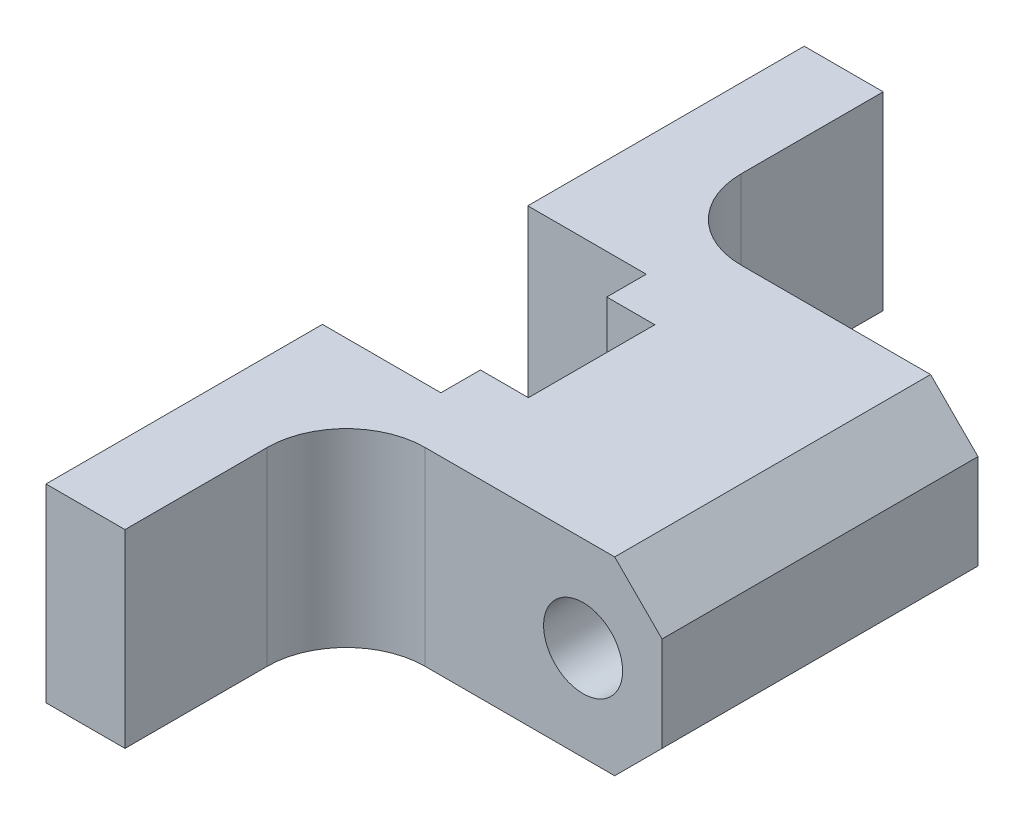
SolidWorks part; units mm, degrees
ref_plane "Спереди" through (0, 0, 0) normal (0, 0, 1) x (1, 0, 0)
ref_plane "Сверху" through (0, 0, 0) normal (0, 1, 0) x (1, 0, 0)
ref_plane "Справа" through (0, 0, 0) normal (1, 0, 0) x (0, 0, -1)
sketch "Эскиз1" plane through (0, 0, 0) normal (1, 0, 0) x (0, 0, -1)
  line L0 (-20, -40.6306) -> (-68.5325, -40.6306) construction
  line L1 (-20, -34.6306) -> (0, -34.6306)
  line L2 (-20, -34.6306) -> (-20, -46.6306)
  line L3 (-20, -46.6306) -> (0, -46.6306)
  line L4 (0, -34.6306) -> (0, -46.6306)
  point P0 (0, 0)
  dimension "D1" = 6
  dimension "D2" = 6
extrude "Вытянуть1" add sketch "Эскиз1" along normal blind 25
sketch "Эскиз5" plane through (0, 0, 20) normal (0, 0, 1) x (1, 0, 0)
  line L0 (0, -34.6306) -> (0, -46.6306) construction
  circle A0 centre (20, -40.6306) radius 2.5
  dimension "D1" = 20
extrude "Вырез-Вытянуть2" cut sketch "Эскиз5" against normal through all
sketch "Эскиз6" plane through (0, 0, 0) normal (-1, 0, 0) x (0, 0, 1)
  line L0 (10, -34.6306) -> (10, -26.4404) construction
  line L1 (20, -34.6306) -> (34, -34.6306)
  line L2 (20, -34.6306) -> (20, -46.6306)
  line L3 (20, -46.6306) -> (34, -46.6306)
  line L4 (34, -34.6306) -> (34, -46.6306)
  line L6 (0, -46.6306) -> (-14, -46.6306)
  line L7 (0, -34.6306) -> (0, -46.6306)
  line L8 (-14, -34.6306) -> (-14, -46.6306)
  line L9 (0, -34.6306) -> (-14, -34.6306)
extrude "Вытянуть2" add sketch "Эскиз6" against normal blind 5
chamfer "Фаска1" distance 3 angle 45 2 edges at (25, -46.6306, 10) (25, -34.6306, 10)
sketch "Эскиз8" plane through (0, -34.6306, 0) normal (0, 1, 0) x (1, 0, 0)
  line L0 (0, -10) -> (-8.3082, -10) construction
  line L2 (0, 14) -> (0, -34) construction
  line L3 (-15.5, -3.5) -> (7.5, -3.5)
  line L4 (-15.5, -3.5) -> (-15.5, -16.5)
  line L5 (-15.5, -16.5) -> (7.5, -16.5)
  line L6 (10.5412, -6) -> (10.5412, -14)
  line L7 (7.5, -14) -> (7.5, -16.5)
  line L9 (7.5, -3.5) -> (7.5, -6)
  line L10 (7.5, -6) -> (10.5412, -6)
  line L11 (7.5, -14) -> (10.5412, -14)
  dimension "D1" = 7.5
  dimension "D2" = 8
extrude "Вытянуть3" cut sketch "Эскиз8" against normal through all
fillet "Скругление1" radius 5 2 edges
